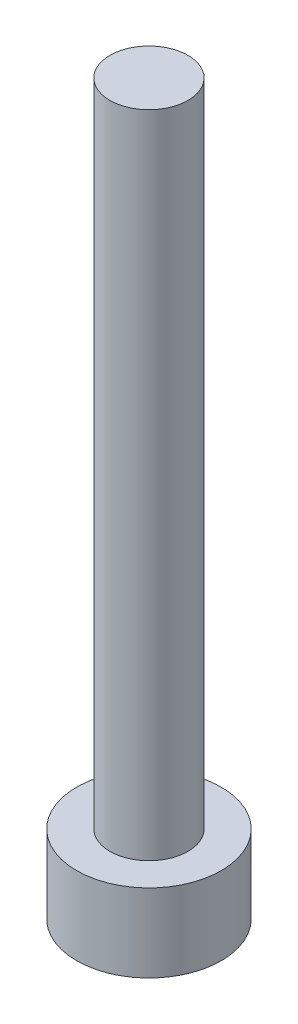
SolidWorks part; units mm, degrees
ref_plane "Front Plane" through (0, 0, 0) normal (0, 0, 1) x (1, 0, 0)
ref_plane "Top Plane" through (0, 0, 0) normal (0, 1, 0) x (1, 0, 0)
ref_plane "Right Plane" through (0, 0, 0) normal (1, 0, 0) x (0, 0, -1)
sketch "Sketch1" plane through (0, 0, 0) normal (0, 1, 0) x (1, 0, 0)
  circle A0 centre (0, 0) radius 2.78
  dimension "D1" = 5.56
extrude "Boss-Extrude1" add sketch "Sketch1" along normal blind 3
sketch "Sketch2" plane through (0, 3, 0) normal (0, 1, 0) x (1, 0, 0)
  circle A0 centre (0, 0) radius 1.5
  dimension "D1" = 3
extrude "Boss-Extrude2" add sketch "Sketch2" along normal blind 25
